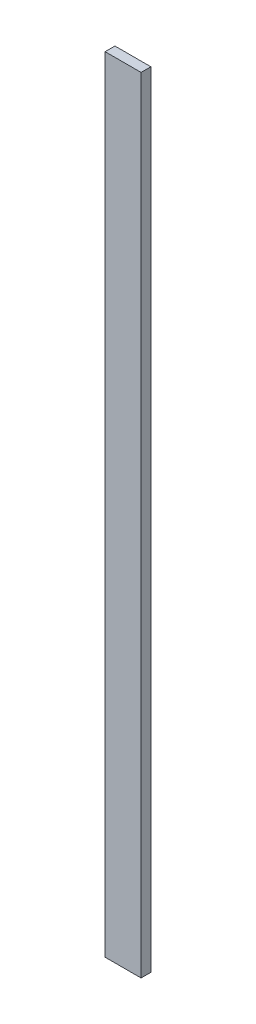
SolidWorks part; units mm, degrees
material "Pine"
ref_plane "Front Plane" through (0, 0, 0) normal (0, 0, 1) x (1, 0, 0)
ref_plane "Top Plane" through (0, 0, 0) normal (0, 1, 0) x (1, 0, 0)
ref_plane "Right Plane" through (0, 0, 0) normal (1, 0, 0) x (0, 0, -1)
sketch "Sketch1" plane through (0, 0, 0) normal (0, 0, 1) x (1, 0, 0)
  line L1 (-15.7045, -51.4848) -> (123.9955, -51.4848)
  line L2 (-15.7045, -51.4848) -> (-15.7045, 2996.5152)
  line L3 (-15.7045, 2996.5152) -> (123.9955, 2996.5152)
  line L4 (123.9955, -51.4848) -> (123.9955, 2996.5152)
  dimension "D1" = 139.7
  dimension "D2" = 3048
extrude "Boss-Extrude1" add sketch "Sketch1" along normal blind 38.1
